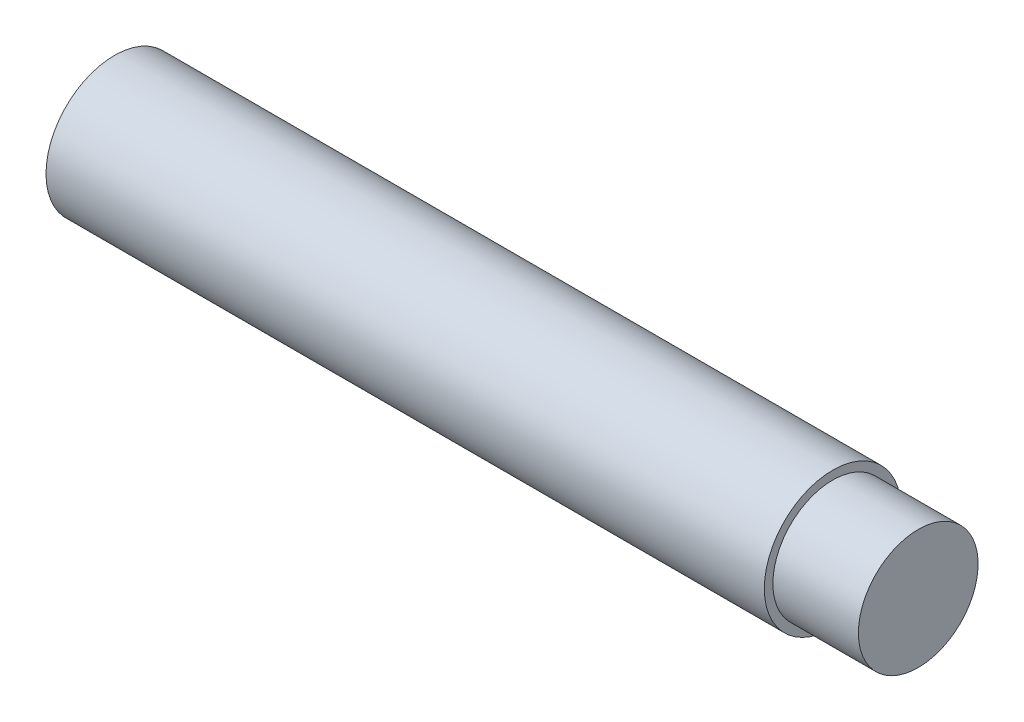
SolidWorks part; units mm, degrees
ref_plane "Front Plane" through (0, 0, 0) normal (0, 0, 1) x (1, 0, 0)
ref_plane "Top Plane" through (0, 0, 0) normal (0, 1, 0) x (1, 0, 0)
ref_plane "Right Plane" through (0, 0, 0) normal (1, 0, 0) x (0, 0, -1)
sketch "Sketch1" plane through (0, 0, 0) normal (0, 0, 1) x (1, 0, 0)
  line L0 (23.5, 0) -> (-23.5, 0)
  line L1 (-23.5, 4) -> (18.5, 4)
  line L2 (-23.5, 4) -> (-23.5, 0)
  line L3 (-23.5, 0) -> (23.5, 0) construction
  line L5 (18.5, 4) -> (18.5, 3.5)
  line L6 (18.5, 3.5) -> (23.5, 3.5)
  line L8 (23.5, 3.5) -> (23.5, 0)
  point P3 (18.2972, 3.3)
  point P7 (26.3023, 6.4865)
  dimension "D1" = 5
  dimension "D2" = 8
  dimension "D3" = 3.5
  dimension "D4" = 47
revolve "Revolve1" add sketch "Sketch1" angle 360 about L3
